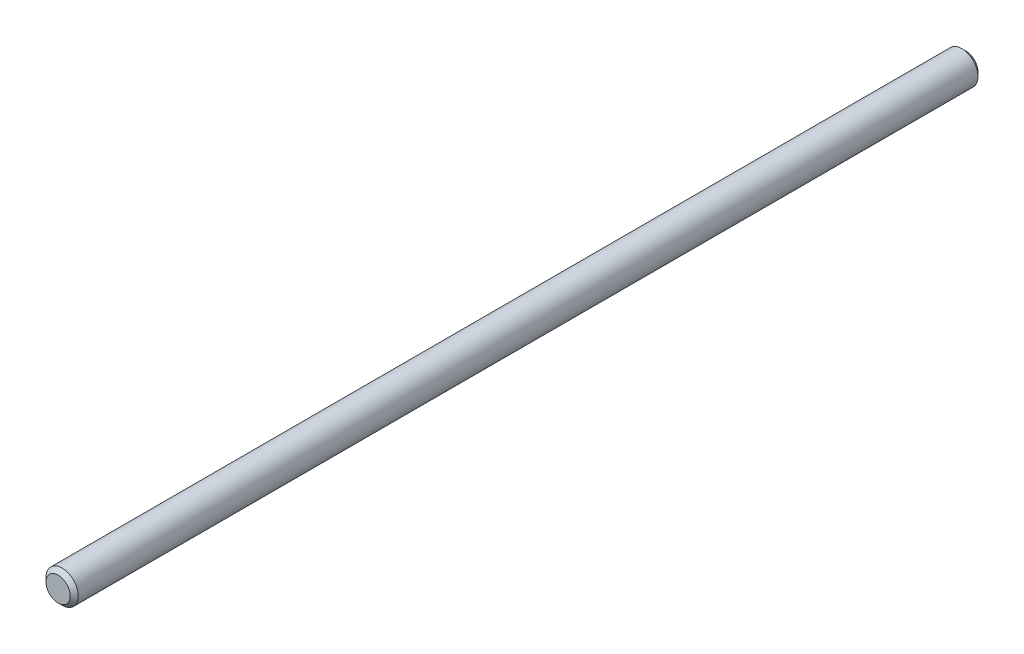
SolidWorks part; units mm, degrees
ref_plane "Front Plane" through (0, 0, 0) normal (0, 0, 1) x (1, 0, 0)
ref_plane "Top Plane" through (0, 0, 0) normal (0, 1, 0) x (1, 0, 0)
ref_plane "Right Plane" through (0, 0, 0) normal (1, 0, 0) x (0, 0, -1)
sketch "Sketch1" plane through (0, 0, 0) normal (0, 0, 1) x (1, 0, 0)
  circle A0 centre (0, 0) radius 4
  dimension "D1" = 8
extrude "Boss-Extrude1" add sketch "Sketch1" along normal blind 225
chamfer "Chamfer1" distance 1 angle 45 2 edges at (4, 0, 225) (4, 0, 0)
